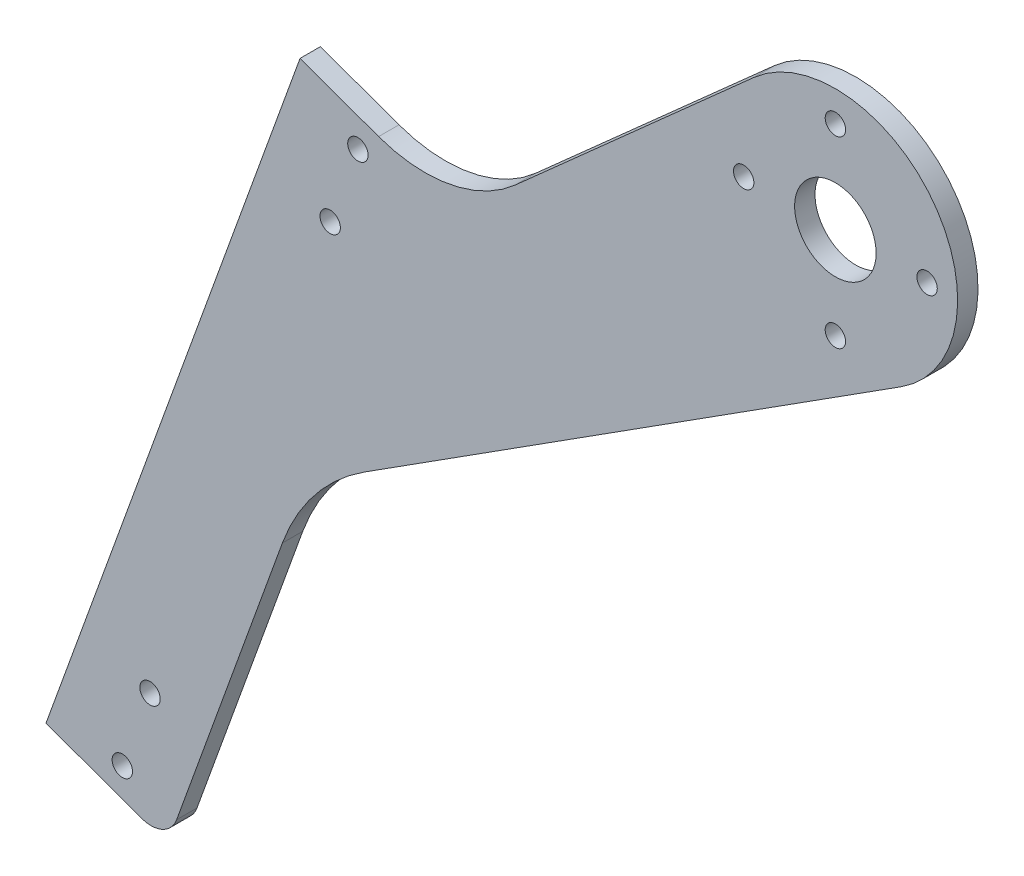
SolidWorks part; units mm, degrees
ref_plane "前视基准面" through (0, 0, 0) normal (0, 0, 1) x (1, 0, 0)
ref_plane "上视基准面" through (0, 0, 0) normal (0, 1, 0) x (1, 0, 0)
ref_plane "右视基准面" through (0, 0, 0) normal (1, 0, 0) x (0, 0, -1)
sketch "Model" plane through (0, 0, 0) normal (0, 0, 1) x (1, 0, 0)
  line L0 (2477.8329, 1762.2088) -> (2490.999, 1757.4493)
  line L1 (2453.6022, 1654.0013) -> (2440.4361, 1658.7609)
  line L2 (2443.8358, 1668.1652) -> (2447.2356, 1677.5696)
  line L3 (2465.1038, 1671.1102) -> (2459.6643, 1656.0632)
  line L4 (2441.8468, 1658.2509) -> (2446.549, 1656.5511)
  line L5 (2465.1038, 1671.1102) -> (2466.6916, 1675.5024)
  line L6 (2465.1038, 1671.1102) -> (2466.6916, 1675.5024)
  line L7 (2477.8329, 1762.2088) -> (2489.4015, 1758.0268)
  line L8 (2509.4996, 1761.8975) -> (2544.6676, 1793.206)
  line L9 (2477.8329, 1762.2088) -> (2490.999, 1757.4493)
  line L10 (2454.5427, 1653.6613) -> (2453.6022, 1654.0013)
  line L11 (2465.1038, 1671.1102) -> (2475.2301, 1699.1217)
  line L12 (2459.6643, 1656.0632) -> (2475.2301, 1699.1217)
  line L13 (2487.3154, 1714.2187) -> (2566.313, 1764.5841)
  line L14 (2477.8329, 1762.2088) -> (2440.4361, 1658.7609)
  arc A0 (2566.313, 1764.5841) -> (2544.6676, 1793.206) centre (2556.6364, 1779.7618) ccw
  circle A1 centre (2482.268, 1743.5922) radius 1.5
  circle A2 centre (2486.3476, 1754.8774) radius 1.5
  circle A3 centre (2451.6706, 1658.9529) radius 1.5
  circle A4 centre (2455.7502, 1670.2382) radius 1.5
  arc A5 (2489.4015, 1758.0268) -> (2509.4996, 1761.8975) centre (2496.2009, 1776.8355) ccw
  arc A6 (2454.5427, 1653.6613) -> (2459.6643, 1656.0632) centre (2455.9026, 1657.4231) ccw
  arc A7 (2487.3154, 1714.2187) -> (2475.2301, 1699.1217) centre (2503.4432, 1688.9226) ccw
  circle A8 centre (2570.1364, 1779.7618) radius 1.5
  circle A9 centre (2556.6364, 1766.2618) radius 1.5
  circle A10 centre (2543.1364, 1779.7618) radius 1.5
  circle A11 centre (2556.6364, 1793.2618) radius 1.5
  circle A12 centre (2556.6364, 1779.7618) radius 6
extrude "凸台-拉伸1" add sketch "Model" along normal blind 3
